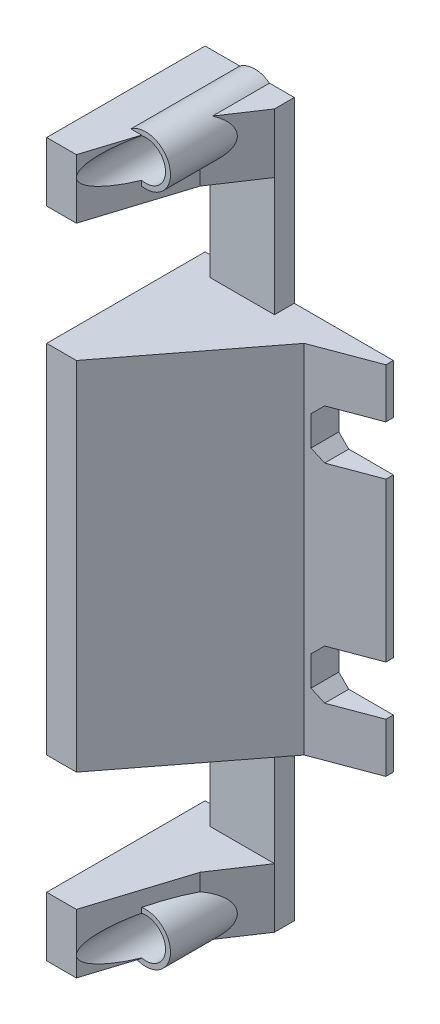
SolidWorks part; units mm, degrees
material "灰色PLA_FDM_原料密度暂定1240"
ref_plane "前视基准面" through (0, 0, 0) normal (0, 0, 1) x (1, 0, 0)
ref_plane "上视基准面" through (0, 0, 0) normal (0, 1, 0) x (1, 0, 0)
ref_plane "右视基准面" through (0, 0, 0) normal (1, 0, 0) x (0, 0, -1)
other "Configuration Table"
sketch "草图1" plane through (0, 0, 0) normal (0, 0, 1) x (1, 0, 0)
  line L0 (37, -72) -> (46, -72)
  line L1 (46, -72) -> (48, -70)
  line L2 (48, -70) -> (48, 70)
  line L3 (48, 70) -> (46, 72)
  line L4 (46, 72) -> (37, 72)
  line L5 (37, 72) -> (35, 70)
  line L6 (35, 70) -> (35, -70)
  line L7 (35, -70) -> (37, -72)
extrude "加厚侧鞍底梁_4mm" add sketch "草图1" along normal blind 4
sketch "草图2" plane through (0, 0, 0) normal (0, 1, 0) x (1, 0, 0)
  line L0 (30, 0) -> (68, 0)
  line L1 (68, 0) -> (68, -1.5)
  line L2 (68, -1.5) -> (56, -6)
  line L3 (56, -6) -> (36, -32)
  line L4 (36, -32) -> (30, -32)
  line L5 (30, -32) -> (30, 0)
extrude "高侧壁6mm_分段缓降斜面_0" add sketch "草图2" along normal blind 72 from offset 36
sketch "草图3" plane through (0, 0, 0) normal (0, 1, 0) x (1, 0, 0)
  line L0 (30, 0) -> (48, 0)
  line L1 (48, 0) -> (48, -4)
  line L2 (48, -4) -> (42, -13)
  line L3 (42, -13) -> (36, -32)
  line L4 (36, -32) -> (30, -32)
  line L5 (30, -32) -> (30, 0)
extrude "高侧壁6mm_分段缓降斜面_66" add sketch "草图3" along normal blind 12 from offset 60
sketch "草图4" plane through (0, 0, 0) normal (0, 1, 0) x (1, 0, 0)
  line L0 (30, 0) -> (48, 0)
  line L1 (48, 0) -> (48, -4)
  line L2 (48, -4) -> (42, -13)
  line L3 (42, -13) -> (36, -32)
  line L4 (36, -32) -> (30, -32)
  line L5 (30, -32) -> (30, 0)
extrude "高侧壁6mm_分段缓降斜面_-66" add sketch "草图4" along normal blind 12 from offset 72
sketch "草图5" plane through (0, 0, 0) normal (0, 0, 1) x (1, 0, 0)
  circle A0 centre (40, -68) radius 1.65
  circle A1 centre (40, 68) radius 1.65
extrude "侧鞍M3贯穿固定孔" cut sketch "草图5" along normal blind 4
sketch "草图7" plane through (0, 0, 0) normal (0, 0, 1) x (1, 0, 0)
  circle A0 centre (40, -68) radius 5
  circle A1 centre (40, -68) radius 1.65
  circle A2 centre (40, 68) radius 5
  circle A3 centre (40, 68) radius 1.65
extrude "螺丝沉台局部加强圈_D10" add sketch "草图7" along normal blind 22
sketch "草图8" plane through (0, 0, 0) normal (0, 0, 1) x (1, 0, 0)
  circle A0 centre (40, -68) radius 4
  circle A1 centre (40, 68) radius 4
extrude "螺丝头及工具沉台_D8_保留4mm底" cut sketch "草图8" along normal blind 32 from offset 4
sketch "草图9" plane through (0, 0, 0) normal (0, 0, 1) x (1, 0, 0)
  line L0 (59, 16) -> (69, 16)
  line L1 (69, 16) -> (71, 18)
  line L2 (71, 18) -> (71, 24)
  line L3 (71, 24) -> (69, 26)
  line L4 (69, 26) -> (59, 26)
  line L5 (59, 26) -> (57, 24)
  line L6 (57, 24) -> (57, 18)
  line L7 (57, 18) -> (59, 16)
  line L8 (59, -26) -> (69, -26)
  line L9 (69, -26) -> (71, -24)
  line L10 (71, -24) -> (71, -18)
  line L11 (71, -18) -> (69, -16)
  line L12 (69, -16) -> (59, -16)
  line L13 (59, -16) -> (57, -18)
  line L14 (57, -18) -> (57, -24)
  line L15 (57, -24) -> (59, -26)
extrude "板内钢索孔侧向敞口避让_14x10" cut sketch "草图9" along normal blind 40
